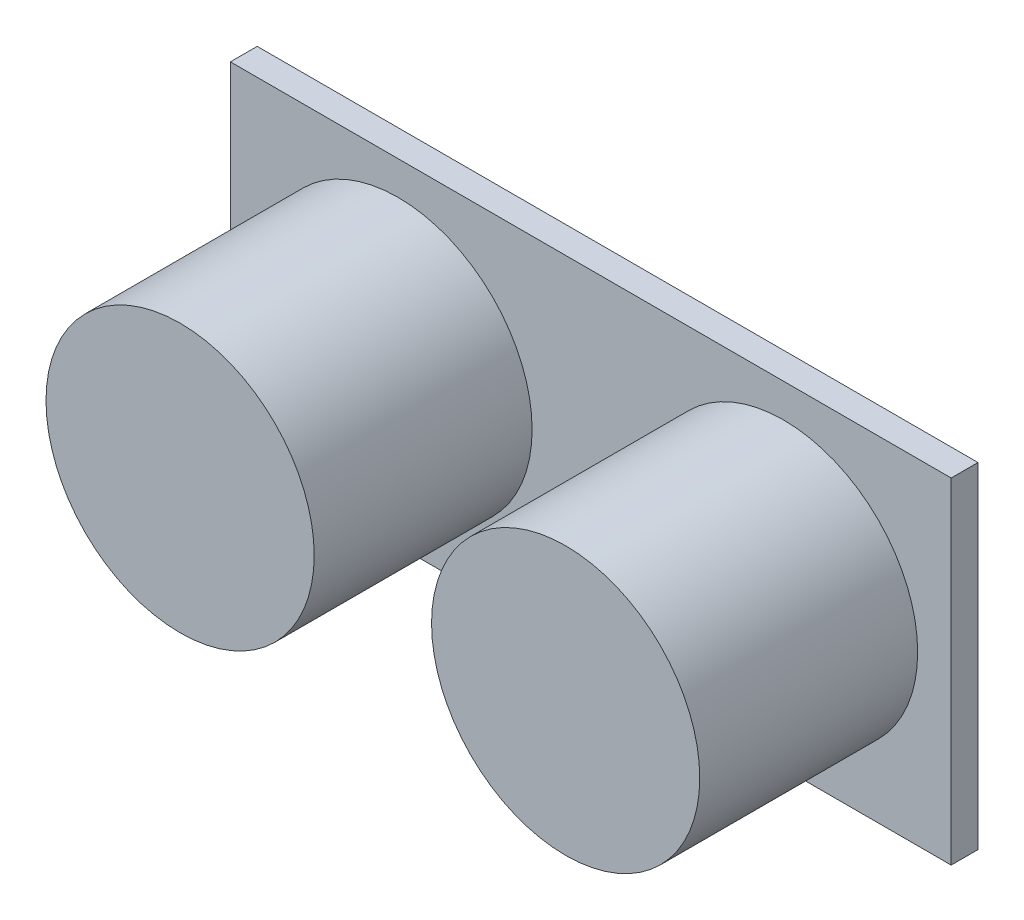
SolidWorks part; units mm, degrees
ref_plane "Front Plane" through (0, 0, 0) normal (0, 0, 1) x (1, 0, 0)
ref_plane "Top Plane" through (0, 0, 0) normal (0, 1, 0) x (1, 0, 0)
ref_plane "Right Plane" through (0, 0, 0) normal (1, 0, 0) x (0, 0, -1)
sketch "Sketch1" plane through (0, 0, 0) normal (0, 0, 1) x (1, 0, 0)
  line L1 (-21.5, -10) -> (21.5, -10)
  line L2 (-21.5, -10) -> (-21.5, 10)
  line L3 (-21.5, 10) -> (21.5, 10)
  line L4 (21.5, -10) -> (21.5, 10)
  line L5 (-21.5, -10) -> (21.5, 10) construction
  line L6 (-21.5, 10) -> (21.5, -10) construction
  point P0 (0, 0)
  dimension "D1" = 43
  dimension "D2" = 20
extrude "Boss-Extrude1" add sketch "Sketch1" along normal blind 1.6
sketch "Sketch2" plane through (0, 0, 1.6) normal (0, 0, 1) x (1, 0, 0)
  line L0 (0, 10) -> (0, -10) construction
  line L1 (21.5, 10) -> (-21.5, 10) construction
  line L2 (-21.5, -10) -> (21.5, -10) construction
  line L4 (-21.5, 10) -> (-21.5, -10) construction
  line L5 (-21.5, 0) -> (21.5, 0) construction
  line L6 (21.5, -10) -> (21.5, 10) construction
  circle A0 centre (-11.5, 0) radius 8
  circle A1 centre (11.5, 0) radius 8
  dimension "D1" = 16
  dimension "D2" = 10
extrude "Boss-Extrude2" add sketch "Sketch2" along normal blind 13
